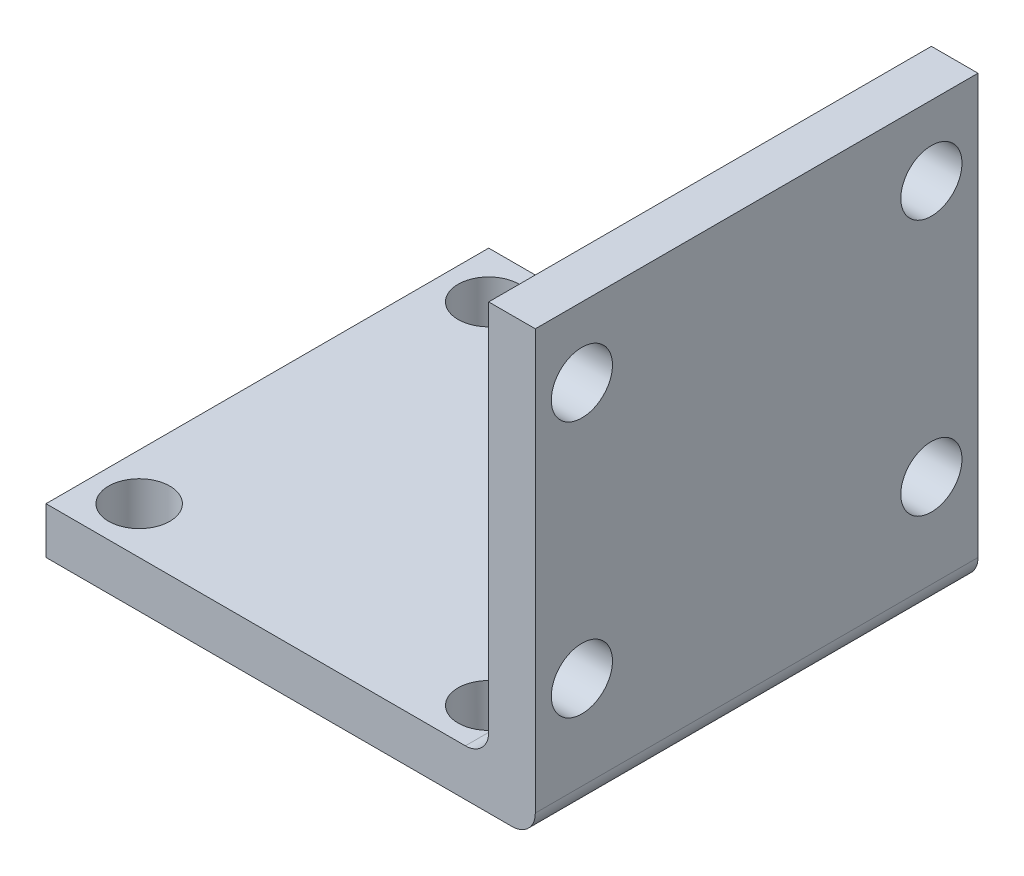
SolidWorks part; units mm, degrees
material "Cast Carbon Steel"
ref_plane "Front" through (0, 0, 0) normal (0, 0, 1) x (1, 0, 0)
ref_plane "Top" through (0, 0, 0) normal (0, 1, 0) x (1, 0, 0)
ref_plane "Right" through (0, 0, 0) normal (1, 0, 0) x (0, 0, -1)
sketch "Sketch1" plane through (0, 0, 0) normal (0, 1, 0) x (1, 0, 0)
  line L1 (0, 0) -> (266.7, 0)
  line L2 (0, 0) -> (0, -241.3)
  line L3 (0, -241.3) -> (266.7, -241.3)
  line L4 (266.7, 0) -> (266.7, -241.3)
  dimension "D1" = 266.7
  dimension "D2" = 241.3
extrude "Boss-Extrude1" add sketch "Sketch1" along normal blind 25.4
sketch "Sketch2" plane through (0, 25.4, 0) normal (0, 1, 0) x (1, 0, 0)
  line L0 (0, -241.3) -> (266.7, -241.3) construction
  line L1 (266.7, 0) -> (241.3, 0)
  line L2 (266.7, 0) -> (266.7, -241.3)
  line L3 (266.7, -241.3) -> (241.3, -241.3)
  line L4 (241.3, 0) -> (241.3, -241.3)
  dimension "D1" = 25.4
extrude "Boss-Extrude2" add sketch "Sketch2" along normal blind 215.9
fillet "Fillet1" radius 12.7 2 edges at (266.7, 0, 120.65) (241.3, 25.4, 120.65)
sketch "Sketch4" plane through (0, 25.4, 0) normal (0, 1, 0) x (1, 0, 0)
  circle A0 centre (25.4, -215.9) radius 16.6751 construction
  circle A1 centre (215.9, -215.9) radius 16.6751 construction
  circle A2 centre (25.4, -25.4) radius 16.6751 construction
  circle A3 centre (215.9, -25.4) radius 16.6751 construction
  circle A4 centre (25.4, -215.9) radius 16.6751
  circle A5 centre (215.9, -215.9) radius 16.6751
  circle A6 centre (25.4, -25.4) radius 16.6751
  circle A7 centre (215.9, -25.4) radius 16.6751
extrude "Cut-Extrude1" cut sketch "Sketch4" against normal through all both and the other way through all
sketch "Sketch5" plane through (241.3, 0, 0) normal (-1, 0, 0) x (0, 0, 1)
  line L0 (8.7249, 0) -> (42.0751, 0) construction
  line L1 (42.0751, 0) -> (199.2249, 0) construction
  line L2 (199.2249, 0) -> (232.5751, 0) construction
  line L3 (0, 241.3) -> (0, 38.1) construction
  line L4 (0, 25.4) -> (241.3, 25.4) construction
  line L6 (0, 241.3) -> (241.3, 241.3) construction
  line L7 (241.3, 241.3) -> (241.3, 38.1) construction
  circle A0 centre (25.4, 63.5) radius 16.6751
  circle A1 centre (25.4, 203.2) radius 16.6751
  circle A2 centre (215.9, 63.5) radius 16.6751
  circle A3 centre (215.9, 203.2) radius 16.6751
  dimension "D1" = 33.3502
  dimension "D2" = 33.3502
  dimension "D3" = 33.3502
  dimension "D4" = 33.3502
  dimension "D5" = 25.4
  dimension "D6" = 38.1
  dimension "D7" = 38.1
  dimension "D8" = 38.1
  dimension "D9" = 38.1
  dimension "D10" = 25.4
  dimension "D11" = 25.4
  dimension "D12" = 25.4
extrude "Cut-Extrude2" cut sketch "Sketch5" against normal through all both and the other way through all
